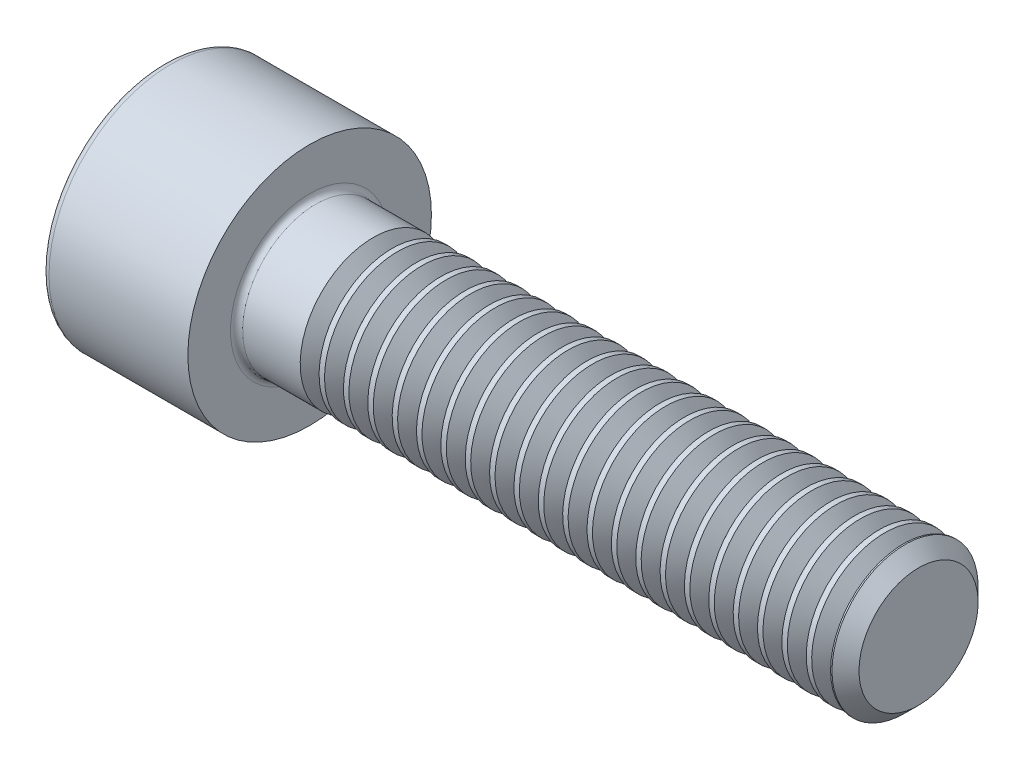
SolidWorks part; units mm, degrees
revolve "Base-Revolve" add sketch "BodySke"
sketch "BodySke" plane through (0, 0, 0) normal (0, 0, 1) x (1, 0, 0)
  line L0 (0, 0) -> (0, 5)
  line L1 (0, 5) -> (6, 5)
  line L2 (6, 5) -> (6, 3)
  line L3 (6, 3) -> (30.4455, 3)
  line L4 (31, 2.4455) -> (31, 0)
  line L5 (31, 0) -> (0, 0)
  line L6 (-31.75, 0) -> (127, 0) construction
  line L8 (31, 2.4455) -> (30.4455, 3)
  line L10 (31, -2.4455) -> (30.4455, -3) construction
  line L11 (7, 9.525) -> (7, 3.175) construction
  line L12 (6, 9.525) -> (6, 3.175) construction
  line L13 (-29, 9.525) -> (-29, 3.175) construction
  dimension "Head_ht" = 6
  dimension "Length" = 25
  dimension "Body_ch_ang" = 45
  dimension "Diameter" = 6
  dimension "Minor_dia" = 4.891
  dimension "Advance" = 1
  dimension "Thread_nom" = 25
  dimension "Thread_length" = 60
  dimension "Head_dia" = 10
cosmetic thread "ThreadCosmetic" [suppressed]
fillet "Fillet1" radius 0.25 1 edges at (6, 0, 3)
fillet "Fillet2" radius 0.3 1 edges at (0, 0, 5)
ref_plane "Plane1" through (0, 0, 0) normal (0, 0, 1) x (1, 0, 0)
ref_plane "Plane2" through (0, 0, 0) normal (0, 1, 0) x (1, 0, 0)
ref_plane "Plane3" through (0, 0, 0) normal (1, 0, 0) x (0, 0, -1)
sketch "Sketch2" plane through (0, 0, 0) normal (0, 0, 1) x (1, 0, 0)
  line L0 (0, 2.542) -> (3, 2.542)
  line L1 (3, 2.542) -> (4.4676, 0)
  line L2 (-31.75, 0) -> (127, 0) construction
  line L3 (4.4676, 0) -> (0, 0)
  line L4 (0, 0) -> (0, 2.542)
  line L6 (0, 0) -> (47.625, 0) construction
  dimension "D1" = 2.542
  dimension "D2" = 60
  dimension "Depth" = 3
revolve "Hex-PreBroach" cut sketch "Sketch2" angle 360 about L6
sketch "Sketch3" plane through (0, 0, 0) normal (-1, 0, 0) x (0, 0.5, 0.866)
  line L0 (1.4676, 2.542) -> (-1.4676, 2.542)
  line L1 (-1.4676, 2.542) -> (-2.9352, 0)
  line L2 (1.4676, 2.542) -> (2.9352, 0)
  line L3 (1.4676, -2.542) -> (2.9352, 0)
  line L4 (1.4676, -2.542) -> (-1.4676, -2.542)
  line L5 (-1.4676, -2.542) -> (-2.9352, 0)
  dimension "D1" = 2.542
  dimension "D2" = 2.542
  dimension "Hex_size" = 5.084
extrude "Hex" cut sketch "Sketch3" against normal blind 3
sketch "ThdSchSke" plane through (0, 0, 0) normal (0, 0, 1) x (1, 0, 0)
  line L0 (9, -2.4455) -> (8.6117, -3)
  line L1 (9, -2.4455) -> (9.3883, -3)
  line L2 (9.3883, -3) -> (9.3883, -3.75)
  line L3 (-3.175, 0) -> (5.1513, 0) construction
  line L4 (0, 4.7) -> (0, -4.7) construction
  line L5 (9.3883, -3.75) -> (8.6117, -3.75)
  line L6 (8.6117, -3.75) -> (8.6117, -3)
  dimension "Thread_minor" = 4.891
  dimension "Diameter" = 6
  dimension "Start" = 9
revolve "ThreadSchematic" cut sketch "ThdSchSke" angle 360 about L3
pattern_linear "ThdSchPat" count 22 spacing 1 along (1, 0, 0) of "ThreadSchematic"
equation "\"D2@Sketch3\" = \"Hex_size@Sketch3\" / 2"
equation "\"D1@Sketch3\" = \"Hex_size@Sketch3\" / 2"
equation "\"D1@Sketch2\" = \"Hex_size@Sketch3\" / 2"
equation "\"Thread_minor@ThreadCosmetic\"  =  \"Minor_dia@BodySke\""
equation "\"Depth@Sketch2\" =  \"Key_eng@Hex\""
equation "\"Thread_length@ThreadCosmetic\" = ((sgn( (\"Length@BodySke\" - \"Advance@BodySke\" * 3.0) - \"Thread_nom@BodySke\" )-1)*( (\"Length@BodySke\" - \"Advance@BodySke\" * 3.0) - \"Thread_nom@BodySke\" ))/-2+ \"Thread_nom@BodySke\""
equation "\"Thread_minor@ThdSchSke\" = \"Minor_dia@BodySke\""
equation "\"Diameter@ThdSchSke\" = \"Diameter@BodySke\""
equation "\"Overcut@ThdSchSke\" = \"Diameter@BodySke\" * 1.25"
equation "\"Start@ThdSchSke\" = \"Head_ht@BodySke\" + \"Length@BodySke\" - \"Thread_length@ThreadCosmetic\"  '---Non-countersunk---"
equation "\"Num_threads@ThdSchPat\" = int( \"Thread_length@ThreadCosmetic\" / \"Advance@BodySke\" + 0.999 )  + 1"
equation "\"Advance@ThdSchPat\" = \"Thread_length@ThreadCosmetic\" /  (\"Num_threads@ThdSchPat\" - 1) 'relax it"
equation "\"Num_threads@ThdSchPat\" = \"Num_threads@ThdSchPat\" - sgn( \"Num_threads@ThdSchPat\" - 1) '---chamfered tips only---"
